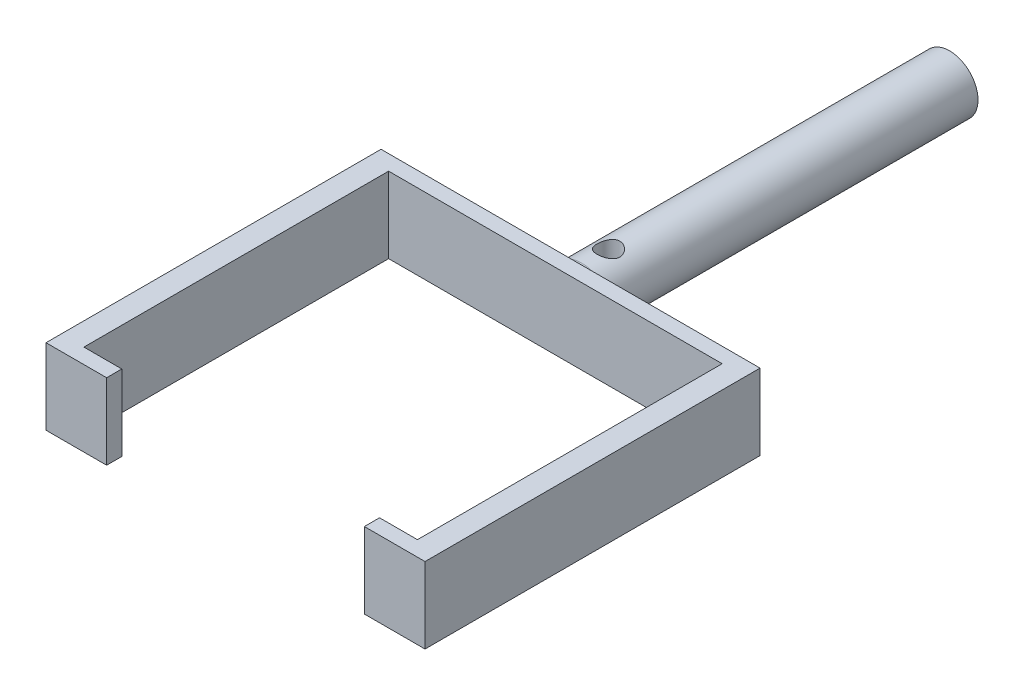
SolidWorks part; units mm, degrees
ref_plane "Plano frontal" through (0, 0, 0) normal (0, 0, 1) x (1, 0, 0)
ref_plane "Plano superior" through (0, 0, 0) normal (0, 1, 0) x (1, 0, 0)
ref_plane "Plano direito" through (0, 0, 0) normal (1, 0, 0) x (0, 0, -1)
sketch "Esboço1" plane through (0, 0, 0) normal (0, 0, 1) x (1, 0, 0)
  circle A0 centre (0, 0) radius 3.75
  dimension "D1" = 7.5
extrude "Ressalto-extrusão1" add sketch "Esboço1" along normal blind 50
sketch "Esboço2" plane through (0, 0, 50) normal (0, 0, 1) x (1, 0, 0)
  line L0 (0, 0) -> (0, 5)
  line L1 (25, 5) -> (-25, 5)
  line L2 (-25, 5) -> (-25, -5)
  line L3 (-25, -5) -> (25, -5)
  line L4 (0, -5) -> (0, 0)
  line L5 (25, 5) -> (25, -5)
  circle M7 centre (0, 0) radius 3.75
  dimension "D1" = 25
  dimension "D2" = 5
  dimension "D3" = 5
extrude "Ressalto-extrusão2" add sketch "Esboço2" along normal blind 2 contours L5 L1 L0 L4 L3 M7 | L3 L4 L0 L1 L2 M7 | L4 L0 M7 | L4 L0 M7
sketch "Esboço3" plane through (0, 0, 52) normal (0, 0, 1) x (1, 0, 0)
  line L0 (-25, 5) -> (-25, -5) construction
  line L1 (-25, 5) -> (-25, -5)
  line L2 (-25, 5) -> (-22, 5)
  line L3 (25, 5) -> (-25, 5) construction
  line L4 (-25, -5) -> (-22, -5)
  line L5 (-25, -5) -> (25, -5) construction
  line L6 (-22, -5) -> (-22, 5)
  line L7 (0, 5) -> (0, -5) construction
  line L8 (25, -5) -> (22, -5)
  line L9 (25, 5) -> (25, -5)
  line L10 (25, 5) -> (22, 5)
  line L11 (22, -5) -> (22, 5)
  dimension "D1" = 3
extrude "Ressalto-extrusão3" add sketch "Esboço3" along normal blind 42.2 contours L6 L2 L1 L4 | L8 L11 L10 L9
sketch "Esboço4" plane through (-22, 0, 0) normal (1, 0, 0) x (0, 0, -1)
  line L0 (-94.2, 5) -> (-94.2, -5)
  line L1 (-94.2, -5) -> (-92.2, -5)
  line L2 (-94.2, -5) -> (-52, -5) construction
  line L3 (-92.2, -5) -> (-92.2, 5)
  line L4 (-94.2, 5) -> (-52, 5) construction
  line L5 (-92.2, 5) -> (-94.2, 5)
  dimension "D1" = 2
extrude "Ressalto-extrusão4" add sketch "Esboço4" along normal blind 5
sketch "Esboço5" plane through (22, 0, 0) normal (-1, 0, 0) x (0, 0, 1)
  line L0 (94.2, -5) -> (94.2, 5) construction
  line L1 (94.2, -5) -> (94.2, 5)
  line L2 (94.2, -5) -> (92.2, -5)
  line L3 (94.2, -5) -> (52, -5) construction
  line L4 (92.2, -5) -> (92.2, 5)
  line L5 (94.2, 5) -> (52, 5) construction
  line L6 (92.2, 5) -> (94.2, 5)
  dimension "D1" = 2
extrude "Ressalto-extrusão5" add sketch "Esboço5" along normal blind 5
fillet "Filete1" radius 1.5 1 edges at (3.75, 0, 50)
sketch "Esboço6" plane through (0, 0, 0) normal (0, 1, 0) x (1, 0, 0)
  line L0 (0, 0) -> (0, -50) construction
  line L2 (0, -50) -> (0, -45)
  circle A1 centre (0, -45) radius 1.5
  dimension "D3" = 3
  dimension "D1" = 50
  dimension "D2" = 5
extrude "Corte-extrusão1" cut sketch "Esboço6" against normal mid plane 10 contours A1
